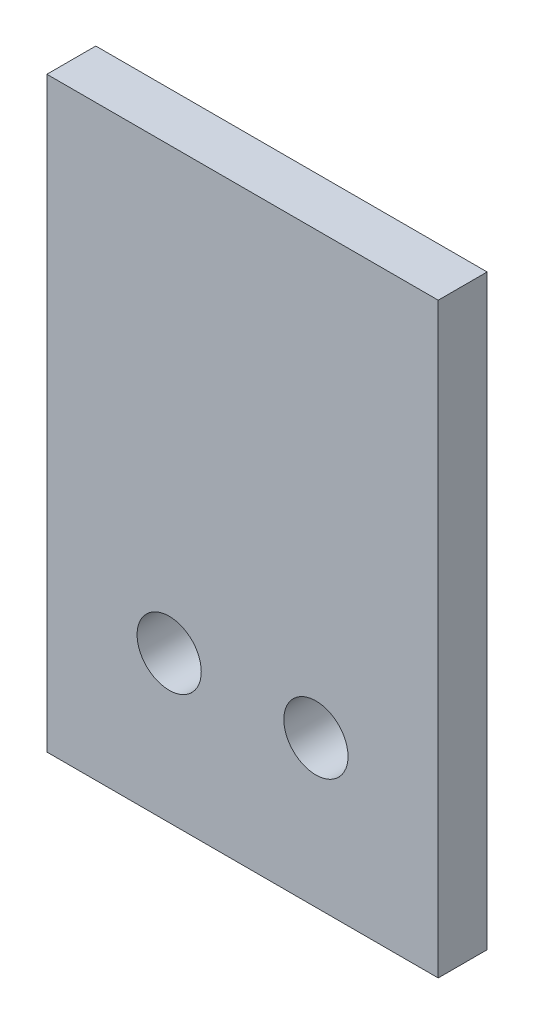
SolidWorks part; units mm, degrees
ref_plane "Front Plane" through (0, 0, 0) normal (0, 0, 1) x (1, 0, 0)
ref_plane "Top Plane" through (0, 0, 0) normal (0, 1, 0) x (1, 0, 0)
ref_plane "Right Plane" through (0, 0, 0) normal (1, 0, 0) x (0, 0, -1)
sketch "Sketch1" plane through (0, 0, 0) normal (0, 0, 1) x (1, 0, 0)
  line L0 (-9.525, 19.05) -> (9.525, 19.05) construction
  line L1 (-25.4, 76.2) -> (25.4, 76.2)
  line L2 (-25.4, 76.2) -> (-25.4, 0)
  line L3 (-25.4, 0) -> (25.4, 0)
  line L4 (25.4, 76.2) -> (25.4, 0)
  line L5 (-25.4, 76.2) -> (25.4, 0) construction
  line L6 (-25.4, 0) -> (25.4, 76.2) construction
  circle A0 centre (9.525, 19.05) radius 4.1656
  circle A1 centre (-9.525, 19.05) radius 4.1656
  point P0 (0, 38.1)
  point P8 (0, 19.05)
  point P9 (0, 0)
  dimension "D5" = 8.3312
  dimension "D1" = 19.05
  dimension "D2" = 50.8
  dimension "D3" = 76.2
  dimension "D4" = 19.05
extrude "Boss-Extrude1" add sketch "Sketch1" along normal blind 6.35
